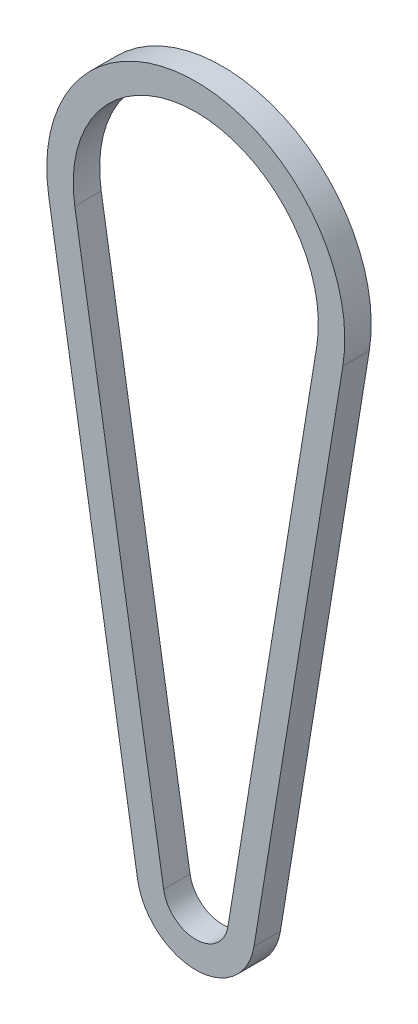
SolidWorks part; units mm, degrees
ref_plane "Front Plane" through (0, 0, 0) normal (0, 0, 1) x (1, 0, 0)
ref_plane "Top Plane" through (0, 0, 0) normal (0, 1, 0) x (1, 0, 0)
ref_plane "Right Plane" through (0, 0, 0) normal (1, 0, 0) x (0, 0, -1)
sketch "Sketch1" plane through (0, 0, 0) normal (0, 0, 1) x (1, 0, 0)
  line L0 (56.5489, 206.7168) -> (22.3889, -3.6358)
  line L1 (-56.5489, 206.7168) -> (-22.3889, -3.6358)
  line L4 (46.5203, 208.3454) -> (12.3603, -2.0072)
  line L5 (-46.5203, 208.3454) -> (-12.3603, -2.0072)
  circle A0 centre (0, 0) radius 22.6822 construction
  circle A1 centre (0, 215.9) radius 57.2897 construction
  arc A2 (-56.5489, 206.7168) -> (56.5489, 206.7168) centre (0, 215.9) cw
  arc A3 (22.3889, -3.6358) -> (-22.3889, -3.6358) centre (0, 0) cw
  arc A6 (-46.5203, 208.3454) -> (46.5203, 208.3454) centre (0, 215.9) cw
  arc A7 (12.3603, -2.0072) -> (-12.3603, -2.0072) centre (0, 0) cw
  dimension "D2" = 45.3644
  dimension "D3" = 114.5794
  dimension "D1" = 215.9
  dimension "D4" = 10.16
extrude "Boss-Extrude1" add sketch "Sketch1" along normal blind 10.16
